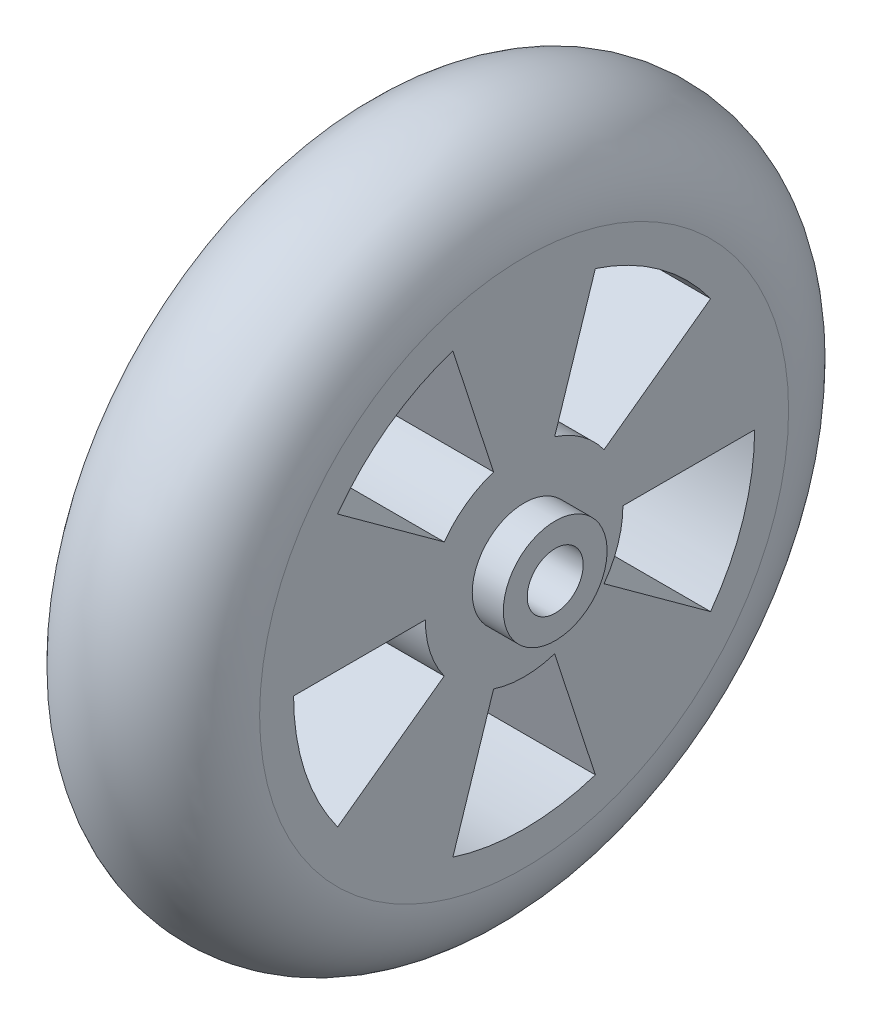
SolidWorks part; units mm, degrees
material "Rubber"
ref_plane "Front Plane" through (0, 0, 0) normal (0, 0, 1) x (1, 0, 0)
ref_plane "Top Plane" through (0, 0, 0) normal (0, 1, 0) x (1, 0, 0)
ref_plane "Right Plane" through (0, 0, 0) normal (1, 0, 0) x (0, 0, -1)
sketch "Sketch1" plane through (0, 0, 0) normal (0, 0, 1) x (1, 0, 0)
  line L0 (0, 25.5) -> (0, 0)
  line L1 (0, 0) -> (20, 0)
  line L2 (20, 0) -> (20, 5)
  line L3 (20, 5) -> (17, 5)
  line L4 (17, 5) -> (17, 25.5)
  line L5 (0, 25.5) -> (17, 25.5) construction
  arc A0 (0, 25.5) -> (17, 25.5) centre (8.5, 25.5) cw
  point P9 (8.5, 34)
  dimension "D1" = 34
  dimension "D2" = 17
  dimension "D3" = 3
  dimension "D4" = 5
revolve "Revolve1" add sketch "Sketch1" angle 360 about L1
sketch "Sketch2" plane through (0, 0, 0) normal (1, 0, 0) x (0, 0, -1)
  circle A0 centre (0, 0) radius 2.7
  dimension "D1" = 5.4
extrude "Cut-Extrude1" cut sketch "Sketch2" along normal through all
sketch "Sketch3" plane through (0, 0, 0) normal (1, 0, 0) x (0, 0, -1)
  line L0 (0, 0) -> (6.8679, 21.1372)
  line L1 (0, 0) -> (17.9804, 13.0635)
  line L2 (0, 0) -> (0, 34) construction
  line L3 (0, 0) -> (22.225, 0)
  line L4 (0, 0) -> (17.9804, -13.0635)
  line L5 (0, 0) -> (6.8679, -21.1372)
  line L6 (0, 0) -> (-6.8679, -21.1372)
  line L7 (0, 0) -> (-17.9804, -13.0635)
  line L8 (0, 0) -> (-22.225, 0)
  line L9 (0, 0) -> (-17.9804, 13.0635)
  line L10 (0, 0) -> (-6.8679, 21.1372)
  circle A0 centre (0, 0) radius 9.525 construction
  circle A1 centre (0, 0) radius 22.225 construction
  arc A2 (2.9434, 9.0588) -> (7.7059, 5.5987) centre (0, 0) cw
  arc A3 (6.8679, 21.1372) -> (17.9804, 13.0635) centre (0, 0) cw
  circle A4 centre (0, 0) radius 34 construction
  arc A5 (22.225, 0) -> (17.9804, -13.0635) centre (0, 0) cw
  arc A6 (9.525, 0) -> (7.7059, -5.5987) centre (0, 0) cw
  arc A7 (6.8679, -21.1372) -> (-6.8679, -21.1372) centre (0, 0) cw
  arc A8 (2.9434, -9.0588) -> (-2.9434, -9.0588) centre (0, 0) cw
  arc A9 (-17.9804, -13.0635) -> (-22.225, 0) centre (0, 0) cw
  arc A10 (-7.7059, -5.5987) -> (-9.525, 0) centre (0, 0) cw
  arc A11 (-17.9804, 13.0635) -> (-6.8679, 21.1372) centre (0, 0) cw
  arc A12 (-7.7059, 5.5987) -> (-2.9434, 9.0588) centre (0, 0) cw
  point P30 (0, 0)
  dimension "D1" = 19.05
  dimension "D2" = 44.45
  dimension "D3" = 18
  dimension "D4" = 36
  dimension "D5" = 5
extrude "Cut-Extrude2" cut sketch "Sketch3" along normal through all contours L9 A12 L10 A11 | A3 L0 A2 L1 | L3 A6 L4 A5 | L5 A8 L6 A7 | L7 A10 L8 A9
